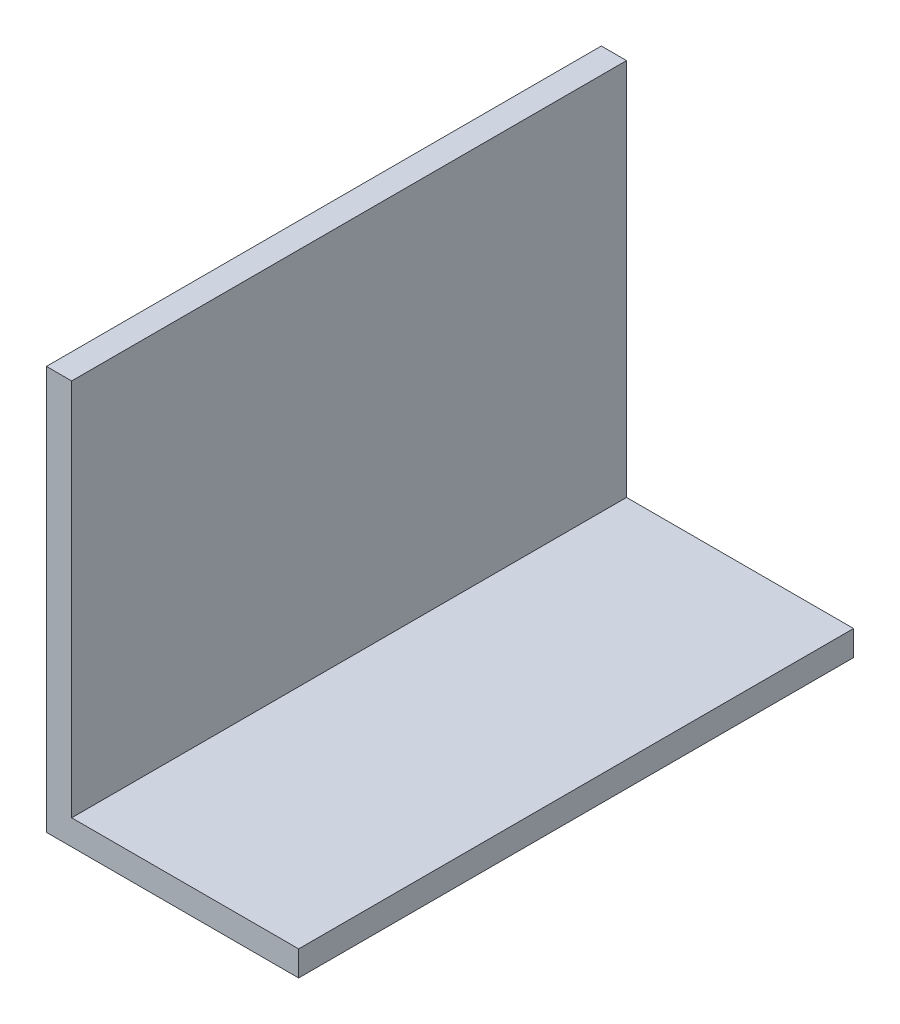
SolidWorks part; units mm, degrees
ref_plane "Front Plane" through (0, 0, 0) normal (0, 0, 1) x (1, 0, 0)
ref_plane "Top Plane" through (0, 0, 0) normal (0, 1, 0) x (1, 0, 0)
ref_plane "Right Plane" through (0, 0, 0) normal (1, 0, 0) x (0, 0, -1)
sketch "Sketch1" plane through (0, 0, 0) normal (0, 0, 1) x (1, 0, 0)
  line L0 (0, 0) -> (0, -80)
  line L1 (0, -80) -> (50, -80)
  line L2 (50, -80) -> (50, -75)
  line L3 (50, -75) -> (5, -75)
  line L4 (5, -75) -> (5, 0)
  line L5 (5, 0) -> (0, 0)
  dimension "D1" = 5
  dimension "D2" = 5
  dimension "D3" = 80
  dimension "D4" = 50
extrude "Boss-Extrude1" add sketch "Sketch1" along normal blind 110
equation "\"D1@Sketch1\"=\"D2@Sketch1\""
